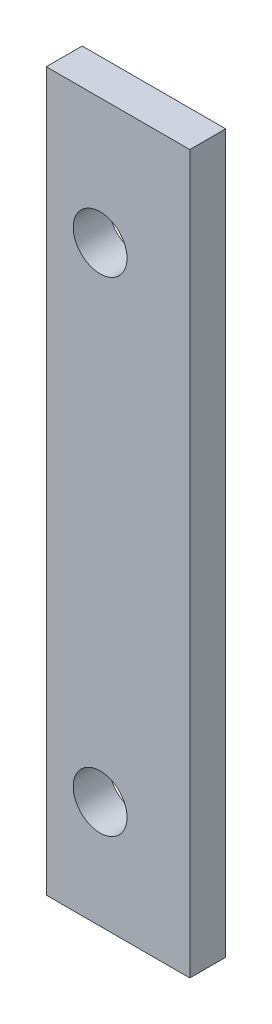
SolidWorks part; units mm, degrees
ref_plane "Front Plane" through (0, 0, 0) normal (0, 0, 1) x (1, 0, 0)
ref_plane "Top Plane" through (0, 0, 0) normal (0, 1, 0) x (1, 0, 0)
ref_plane "Right Plane" through (0, 0, 0) normal (1, 0, 0) x (0, 0, -1)
sketch "Sketch1" plane through (0, 0, 0) normal (0, 0, 1) x (1, 0, 0)
  line L1 (4, -20) -> (-4, -20)
  line L2 (4, -20) -> (4, 20)
  line L3 (4, 20) -> (-4, 20)
  line L4 (-4, -20) -> (-4, 20)
  line L5 (4, -20) -> (-4, 20) construction
  line L6 (4, 20) -> (-4, -20) construction
  point P0 (0, 0)
  dimension "D1" = 40
  dimension "D2" = 8
extrude "Boss-Extrude1" add sketch "Sketch1" along normal blind 2
sketch "Sketch2" plane through (0, 0, 2) normal (0, 0, 1) x (1, 0, 0)
  line L0 (-4, -20) -> (4, -20) construction
  line L1 (-4, 20) -> (-4, -20) construction
  circle A0 centre (-1, -14) radius 1.5
  circle A1 centre (-1, 13) radius 1.5
  dimension "D1" = 3
  dimension "D2" = 3
  dimension "D3" = 6
  dimension "D4" = 27
  dimension "D5" = 3
  dimension "D6" = 3
extrude "Cut-Extrude1" cut sketch "Sketch2" against normal blind 2
